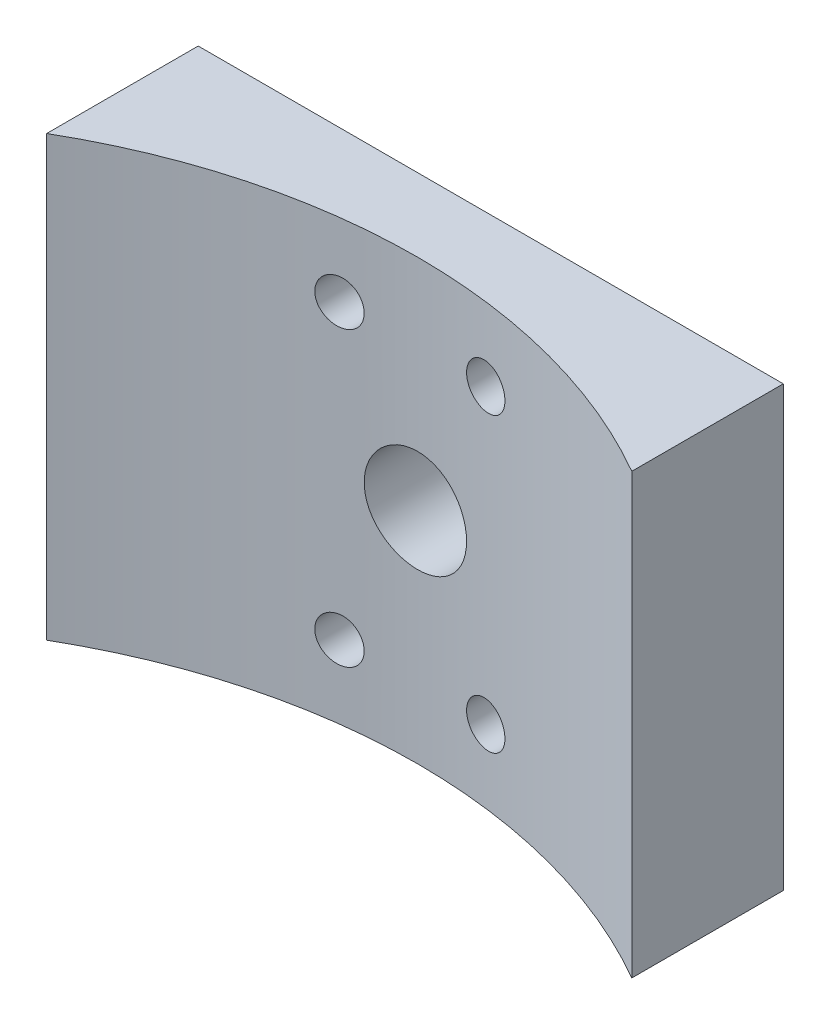
SolidWorks part; units mm, degrees
ref_plane "Ön Düzlem" through (0, 0, 0) normal (0, 0, 1) x (1, 0, 0)
ref_plane "Üst Düzlem" through (0, 0, 0) normal (0, 1, 0) x (1, 0, 0)
ref_plane "Sağ Düzlem" through (0, 0, 0) normal (1, 0, 0) x (0, 0, -1)
sketch "Çizim1" plane through (0, 0, 0) normal (0, 1, 0) x (1, 0, 0)
  line L1 (20, 40) -> (20, 34.641)
  line L2 (20, 40) -> (20, 45)
  line L3 (20, 45) -> (-20, 45)
  line L4 (-20, 34.641) -> (-20, 45)
  arc A0 (20, 34.641) -> (-20, 34.641) centre (0, 0) ccw
extrude "Yükseklik-Ekstrüzyon1" add sketch "Çizim1" along normal blind 30
sketch "Çizim2" plane through (0, 0, 0) normal (0, 0, 1) x (1, 0, 0)
  line L0 (0, 0) -> (0, 5)
  line L1 (0, 5) -> (-5, 5)
  line L2 (0, 5) -> (5, 5)
  line L3 (0, 30) -> (0, 25)
  line L4 (20, 30) -> (-20, 30) construction
  line L5 (0, 25) -> (5, 25)
  line L6 (0, 25) -> (-5, 25)
  circle A2 centre (0, 15) radius 3.5
  circle A3 centre (-5, 5) radius 1.5
  circle A4 centre (5, 5) radius 1.5
  circle A5 centre (-5, 25) radius 1.5
  circle A6 centre (5, 25) radius 1.5
extrude "Kes-Ekstrüzyon1" cut sketch "Çizim2" against normal through all
